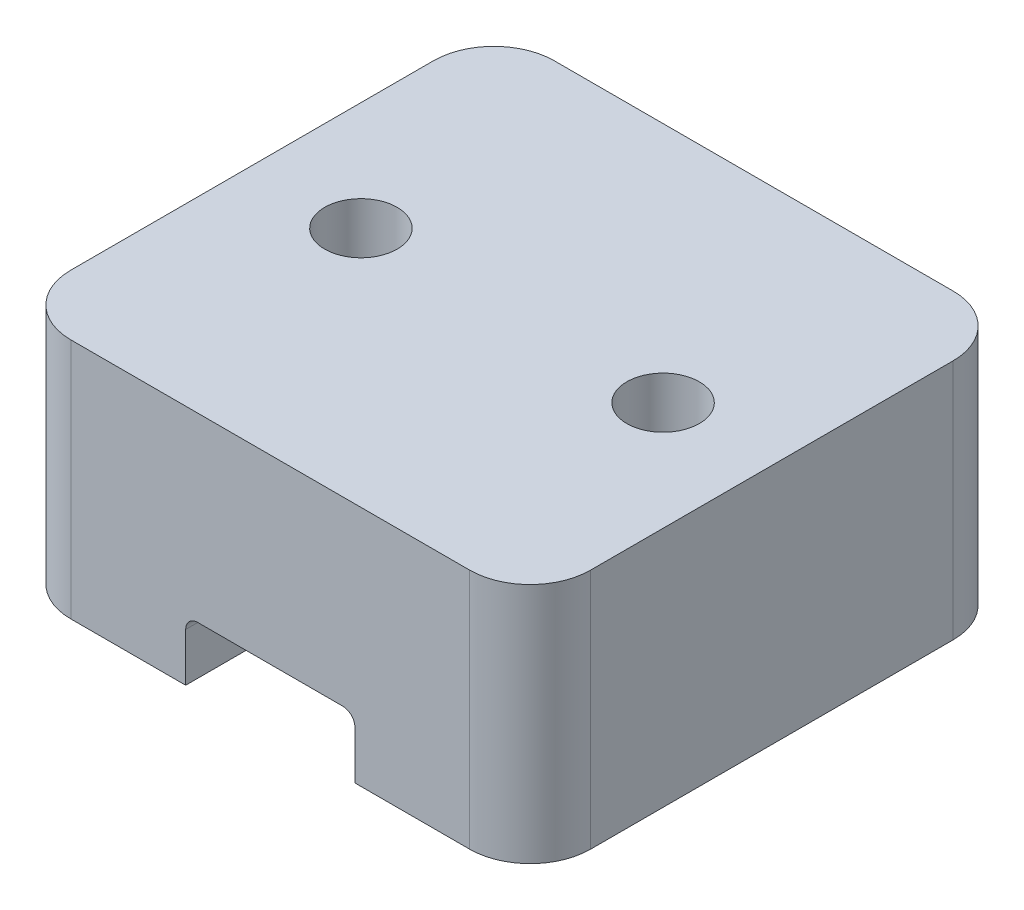
SolidWorks part; units mm, degrees
ref_plane "Front" through (0, 0, 0) normal (0, 0, 1) x (1, 0, 0)
ref_plane "Top" through (0, 0, 0) normal (0, 1, 0) x (1, 0, 0)
ref_plane "Right" through (0, 0, 0) normal (1, 0, 0) x (0, 0, -1)
sketch "Sketch1" plane through (0, 0, 0) normal (0, 1, 0) x (1, 0, 0)
  line L1 (0, 0) -> (43, 0)
  line L2 (0, 0) -> (0, 40)
  line L3 (0, 40) -> (43, 40)
  line L4 (43, 0) -> (43, 40)
  dimension "D1" = 43
  dimension "D2" = 40
extrude "Boss-Extrude1" add sketch "Sketch1" along normal blind 20
sketch "Sketch2" plane through (0, 20, 0) normal (0, 1, 0) x (1, 0, 0)
  line L0 (0, 40) -> (0, 0) construction
  line L1 (0, 0) -> (43, 0) construction
  circle A0 centre (9, 20) radius 3
  circle A1 centre (34, 20) radius 3
  dimension "D1" = 6
  dimension "D2" = 6
  dimension "D3" = 9
  dimension "D4" = 25
  dimension "D5" = 20
extrude "Cut-Extrude1" cut sketch "Sketch2" against normal up to next
fillet "Fillet1" radius 5 4 edges at (0, 10, -40) (43, 10, -40) (43, 10, 0) (0, 10, 0)
sketch "Sketch3" plane through (0, 0, 0) normal (0, 0, 1) x (1, 0, 0)
  line L0 (5, 0) -> (38, 0) construction
  line L1 (14.5, 0) -> (28.5, 0)
  line L2 (14.5, 0) -> (14.5, 5)
  line L3 (14.5, 5) -> (28.5, 5)
  line L4 (28.5, 0) -> (28.5, 5)
  point P6 (21.5, 0)
  point P7 (21.5, 0)
  dimension "D1" = 5
  dimension "D2" = 14
extrude "Cut-Extrude2" cut sketch "Sketch3" against normal up to next
fillet "Fillet2" radius 1 2 edges at (28.5, 5, -20) (14.5, 5, -20)
